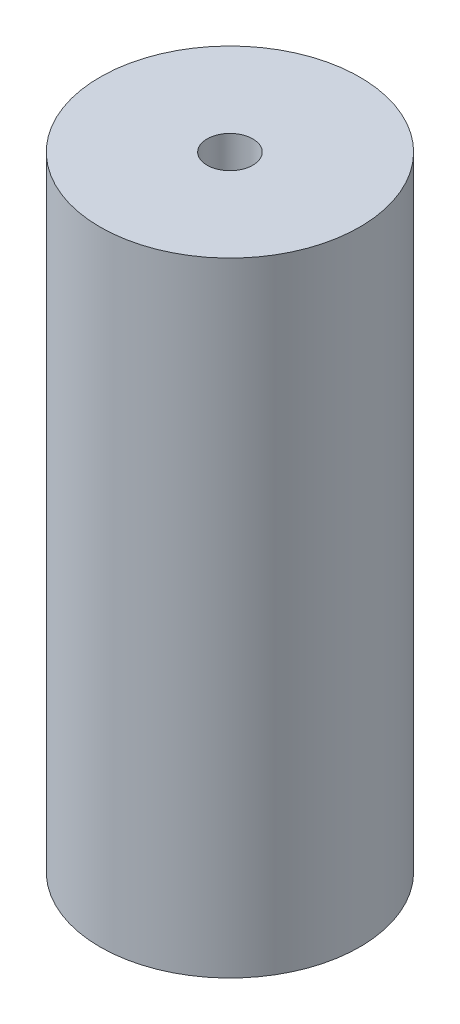
SolidWorks part; units mm, degrees
ref_plane "Plan de face" through (0, 0, 0) normal (0, 0, 1) x (1, 0, 0)
ref_plane "Plan de dessus" through (0, 0, 0) normal (0, 1, 0) x (1, 0, 0)
ref_plane "Plan de droite" through (0, 0, 0) normal (1, 0, 0) x (0, 0, -1)
sketch "Esquisse1" plane through (0, 0, 0) normal (0, 1, 0) x (1, 0, 0)
  circle A0 centre (0, 0) radius 12.5
  dimension "D1" = 25
extrude "Boss.-Extru.1" add sketch "Esquisse1" along normal blind 60
sketch "Esquisse2" plane through (0, 0, 0) normal (0, -1, 0) x (1, 0, 0)
  circle A0 centre (0, 0) radius 2.2
extrude "Enlèv. mat.-Extru.1" cut sketch "Esquisse2" against normal blind 60 contours A0
